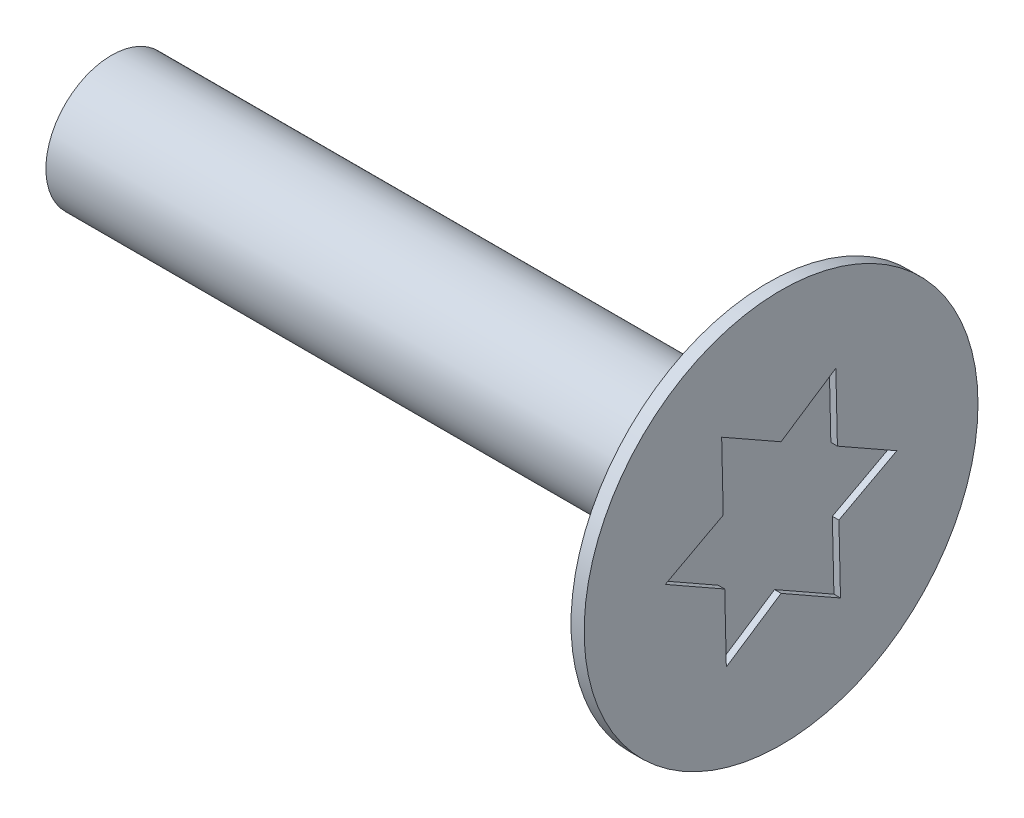
SolidWorks part; units mm, degrees
ref_plane "Alzado" through (0, 0, 0) normal (0, 0, 1) x (1, 0, 0)
ref_plane "Planta" through (0, 0, 0) normal (0, 1, 0) x (1, 0, 0)
ref_plane "Vista lateral" through (0, 0, 0) normal (1, 0, 0) x (0, 0, -1)
sketch "Croquis1" plane through (0, 0, 0) normal (1, 0, 0) x (0, 0, -1)
  circle A1 centre (0, 0) radius 0.5
  dimension "D1" = 1
extrude "Extruir1" add sketch "Croquis1" along normal blind 5
sketch "Croquis2" plane through (5, 0, 0) normal (1, 0, 0) x (0, 0, -1)
  circle A0 centre (0, 0) radius 1.5
  dimension "D1" = 3
extrude "Extruir2" add sketch "Croquis2" along normal blind 0.1
sketch "Croquis3" plane through (5.1, 0, 0) normal (1, 0, 0) x (0, 0, -1)
  line L0 (0.4171, 0.7768) -> (0.4291, 0.2566)
  line L7 (0.4291, 0.2566) -> (0.8817, 0)
  line L8 (0.8817, 0) -> (0.4405, -0.2365)
  line L9 (0.4405, -0.2365) -> (0.4525, -0.7566)
  line L10 (0.4525, -0.7566) -> (0, -0.5)
  line L11 (0, -0.5) -> (-0.4171, -0.7768)
  line L12 (-0.4171, -0.7768) -> (-0.4291, -0.2566)
  line L13 (-0.4291, -0.2566) -> (-0.8817, 0)
  line L14 (-0.8817, 0) -> (-0.4405, 0.2365)
  line L15 (-0.4405, 0.2365) -> (-0.4525, 0.7566)
  line L16 (-0.4525, 0.7566) -> (0, 0.5)
  line L17 (0, 0.5) -> (0.4171, 0.7768)
  circle A0 centre (0, 0) radius 0.8817 construction
  circle A1 centre (0, 0) radius 0.5 construction
  dimension "D3" = 1
  dimension "D1" = 1.7633
extrude "Extruir3" cut sketch "Croquis3" against normal blind 0.05
